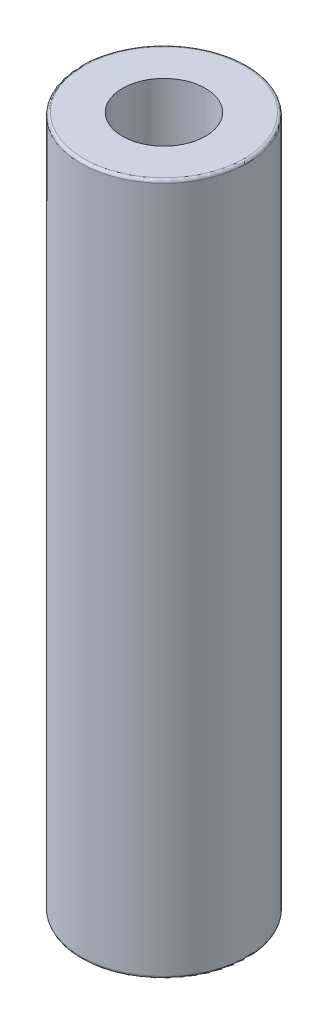
SolidWorks part; units mm, degrees
ref_plane "正面" through (0, 0, 0) normal (0, 0, 1) x (1, 0, 0)
ref_plane "平面" through (0, 0, 0) normal (0, 1, 0) x (1, 0, 0)
ref_plane "右側面" through (0, 0, 0) normal (1, 0, 0) x (0, 0, -1)
sketch "ｽｹｯﾁ1" plane through (0, 0, 0) normal (0, 1, 0) x (1, 0, 0)
  circle A0 centre (0, 0) radius 3
  circle A1 centre (0, 0) radius 1.5
  dimension "D1" = 3
  dimension "D2" = 6
extrude "ﾎﾞｽ - 押し出し1" add sketch "ｽｹｯﾁ1" along normal blind 25
fillet "ﾌｨﾚｯﾄ1" radius 0.1 2 edges at (0, 25, 3) (0, 0, 3)
